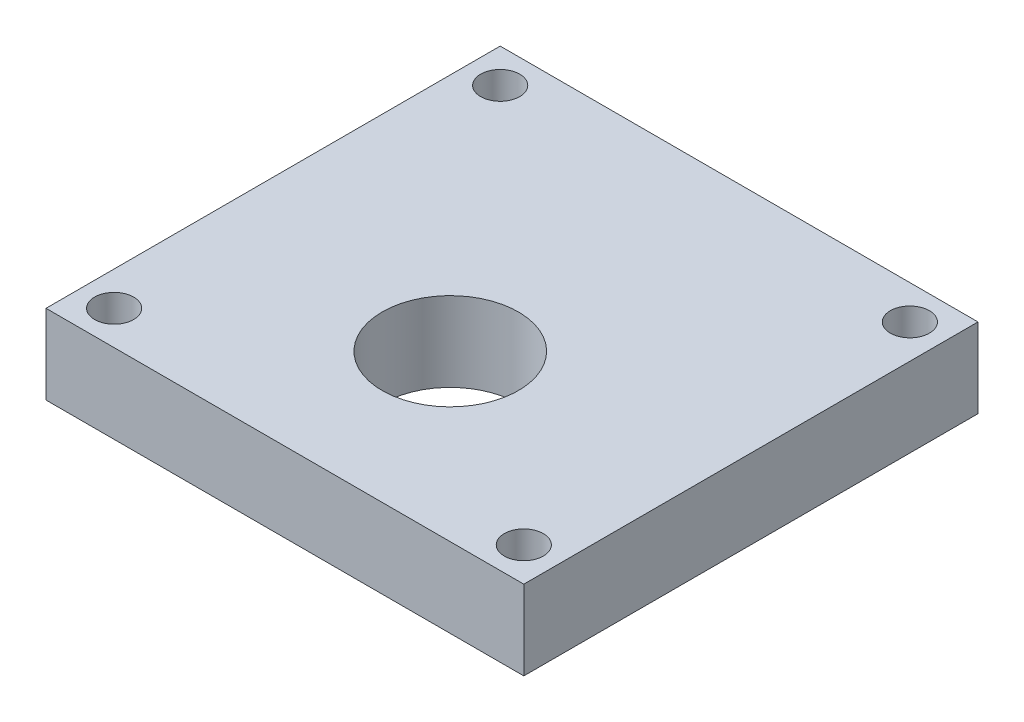
SolidWorks part; units mm, degrees
ref_plane "Front Plane" through (0, 0, 0) normal (0, 0, 1) x (1, 0, 0)
ref_plane "Top Plane" through (0, 0, 0) normal (0, 1, 0) x (1, 0, 0)
ref_plane "Right Plane" through (0, 0, 0) normal (1, 0, 0) x (0, 0, -1)
sketch "Sketch1" plane through (0, 0, 0) normal (0, 0, 1) x (1, 0, 0)
  line L7 (-8.89, 40.64) -> (-8.89, 46.99)
  line L9 (44.5516, 40.64) -> (44.5516, 46.99)
  line L15 (44.5516, 46.99) -> (44.5516, 49.53)
  line L16 (44.5516, 49.53) -> (-8.89, 49.53)
  line L17 (-8.89, 49.53) -> (-8.89, 46.99)
  line L18 (44.5516, 40.64) -> (-8.89, 40.64)
  point P0 (0, 0)
  dimension "D5" = 2.54
extrude "Boss-Extrude1" add sketch "Sketch1" along normal blind 50.8
sketch "Sketch2" plane through (0, 49.53, 0) normal (0, 1, 0) x (1, 0, 0)
  line L1 (28.8798, -36.351) -> (28.8798, -14.351) construction
  line L2 (28.8798, -14.351) -> (6.8798, -14.351) construction
  line L6 (44.5516, 0) -> (-8.89, 0) construction
  circle A4 centre (17.8798, -32.351) radius 7.62
  dimension "D10" = 15.24
  dimension "D8" = 14.351
extrude "Cut-Extrude1" cut sketch "Sketch2" against normal up to next
sketch "Sketch3" plane through (0, 49.53, 0) normal (0, 1, 0) x (1, 0, 0)
  line L0 (40.7416, -46.99) -> (40.7416, -3.81) construction
  line L1 (44.5516, -50.8) -> (-8.89, -50.8) construction
  line L2 (44.5516, -50.8) -> (44.5516, 0) construction
  line L3 (44.5516, 0) -> (-8.89, 0) construction
  line L4 (-8.89, -50.8) -> (-8.89, 0) construction
  line L5 (40.7416, -3.81) -> (-5.08, -3.81) construction
  line L6 (-5.08, -46.99) -> (-5.08, -3.81) construction
  line L7 (40.7416, -46.99) -> (-5.08, -46.99) construction
  circle A0 centre (40.7416, -46.99) radius 2.1828
  circle A1 centre (-5.08, -46.99) radius 2.1828
  circle A2 centre (-5.08, -3.81) radius 2.1828
  circle A3 centre (40.7416, -3.81) radius 2.1828
  dimension "D2" = 4.3656
  dimension "D3" = 4.3656
  dimension "D4" = 4.3656
  dimension "D5" = 4.3656
  dimension "D1" = 3.81
extrude "Cut-Extrude2" cut sketch "Sketch3" against normal through all
